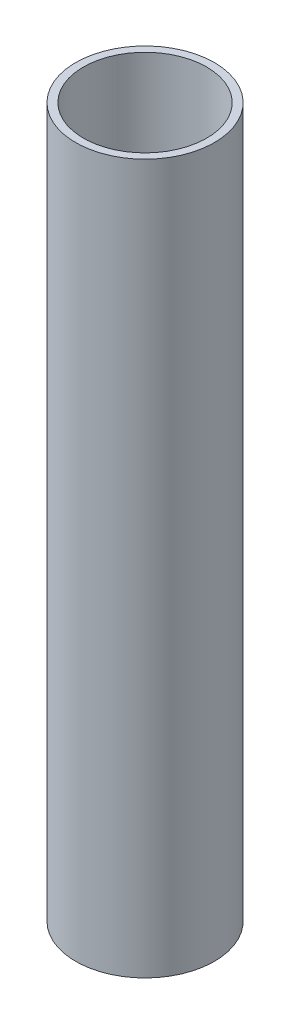
SolidWorks part; units mm, degrees
ref_plane "Front Plane" through (0, 0, 0) normal (0, 0, 1) x (1, 0, 0)
ref_plane "Top Plane" through (0, 0, 0) normal (0, 1, 0) x (1, 0, 0)
ref_plane "Right Plane" through (0, 0, 0) normal (1, 0, 0) x (0, 0, -1)
sketch "Sketch2" plane through (0, 0, 0) normal (0, 1, 0) x (1, 0, 0)
  circle A0 centre (0, 0) radius 20.32
  circle A1 centre (0, 0) radius 22.86
  dimension "D1" = 2.54
extrude "Boss-Extrude1" add sketch "Sketch2" along normal blind 233.68
